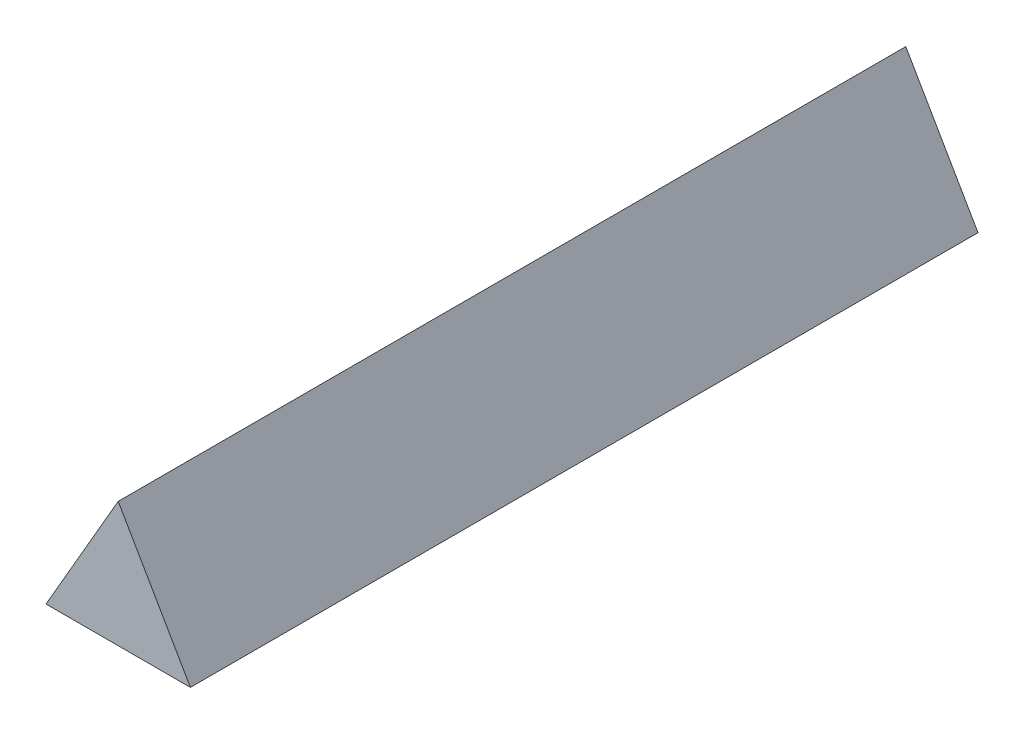
SolidWorks part; units mm, degrees
ref_plane "Front Plane" through (0, 0, 0) normal (0, 0, 1) x (1, 0, 0)
ref_plane "Top Plane" through (0, 0, 0) normal (0, 1, 0) x (1, 0, 0)
ref_plane "Right Plane" through (0, 0, 0) normal (1, 0, 0) x (0, 0, -1)
sketch "Sketch1" plane through (0, 0, 0) normal (0, 0, 1) x (1, 0, 0)
  line L0 (-132.9848, 115.3535) -> (-137.1758, 108.0945)
  line L1 (-137.1758, 108.0945) -> (-128.7938, 108.0945)
  line L2 (-128.7938, 108.0945) -> (-132.9848, 115.3535)
  dimension "D1" = 8.382
extrude "Boss-Extrude1" add sketch "Sketch1" along normal blind 45.72
sketch "Sketch3" plane through (0, 0, 0) normal (0, 0, -1) x (-1, 0, 0)
  line L0 (132.9848, 115.3535) -> (132.9848, 110.5142) construction
  line L1 (132.9848, 110.5142) -> (128.7938, 108.0945) construction
  line L2 (132.9848, 110.5142) -> (137.1758, 108.0945) construction
  circle A0 centre (132.9848, 110.5142) radius 2
  dimension "D1" = 4
extrude "Cut-Extrude1" cut sketch "Sketch3" against normal blind 8
sketch "Sketch4" plane through (-149.6882, 86.4225, 0) normal (-0.866, 0.5, 0) x (0, 0, 1)
  line L0 (0, 29.2156) -> (45.72, 29.2156) construction
  line L1 (0, 33.4066) -> (0, 25.0246) construction
  line L2 (45.72, 33.4066) -> (45.72, 25.0246) construction
  circle A0 centre (4, 29.2156) radius 1.27
  dimension "D1" = 2.54
  dimension "D2" = 4
extrude "Cut-Extrude2" cut sketch "Sketch4" against normal blind 2.54
